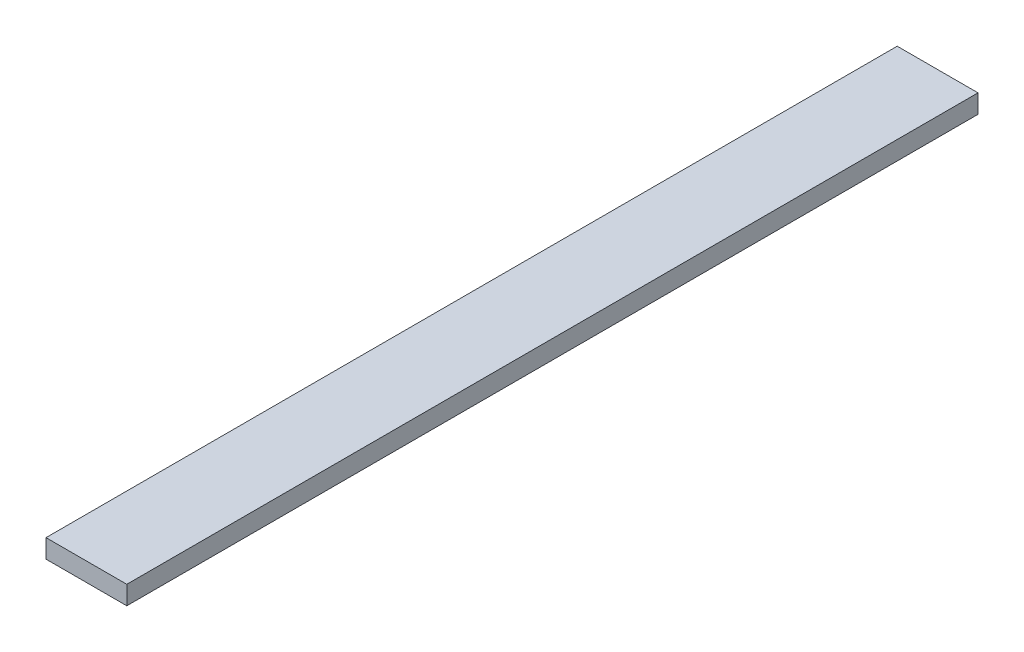
SolidWorks part; units mm, degrees
ref_plane "Front Plane" through (0, 0, 0) normal (0, 0, 1) x (1, 0, 0)
ref_plane "Top Plane" through (0, 0, 0) normal (0, 1, 0) x (1, 0, 0)
ref_plane "Right Plane" through (0, 0, 0) normal (1, 0, 0) x (0, 0, -1)
sketch "Sketch1" plane through (0, 0, 0) normal (0, 0, 1) x (1, 0, 0)
  line L1 (0, 0) -> (41.275, 0)
  line L2 (0, 0) -> (0, 9.525)
  line L3 (0, 9.525) -> (41.275, 9.525)
  line L4 (41.275, 0) -> (41.275, 9.525)
  dimension "D1" = 9.525
  dimension "D2" = 41.275
extrude "Boss-Extrude1" add sketch "Sketch1" along normal blind 434.848
